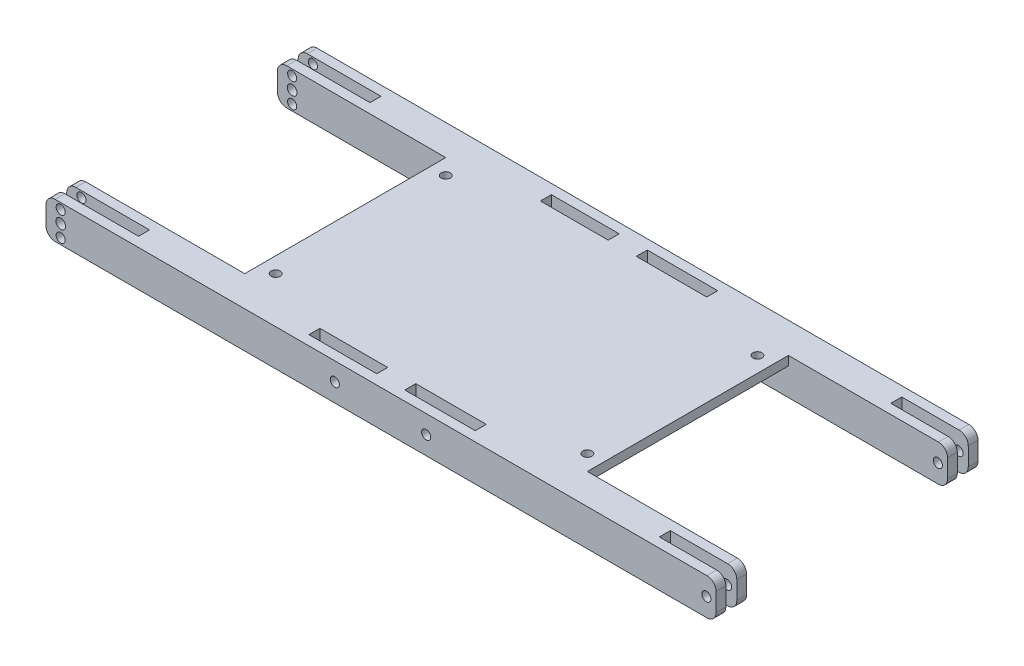
SolidWorks part; units mm, degrees
ref_plane "Front Plane" through (0, 0, 0) normal (0, 0, 1) x (1, 0, 0)
ref_plane "Top Plane" through (0, 0, 0) normal (0, 1, 0) x (1, 0, 0)
ref_plane "Right Plane" through (0, 0, 0) normal (1, 0, 0) x (0, 0, -1)
sketch "Sketch1" plane through (0, 0, 0) normal (0, 0, 1) x (1, 0, 0)
  line L0 (109.8741, 43.7425) -> (110.0523, 43.8945)
  line L1 (-103.9477, 43.8945) -> (110.0523, 43.8945)
  line L2 (-106.9477, 40.8945) -> (-106.9477, 34.8945)
  line L3 (-103.9477, 31.8945) -> (110.0523, 31.8945)
  line L4 (113.0523, 40.8945) -> (113.0523, 34.8945)
  arc A0 (-103.9477, 43.8945) -> (-106.9477, 40.8945) centre (-103.9477, 40.8945) ccw
  arc A1 (-106.9477, 34.8945) -> (-103.9477, 31.8945) centre (-103.9477, 34.8945) ccw
  arc A2 (110.0523, 31.8945) -> (113.0523, 34.8945) centre (110.0523, 34.8945) ccw
  arc A3 (110.0523, 43.8945) -> (113.0523, 40.8945) centre (110.0523, 40.8945) cw
  circle A4 centre (-102.1259, 37.8955) radius 1.6
  circle A5 centre (-102.1259, 41.8955) radius 1.5
  circle A6 centre (-102.1259, 33.8955) radius 1.5
  circle A7 centre (109.8742, 37.8918) radius 1.5
  circle A8 centre (-12.1259, 37.8955) radius 1.5
  circle A9 centre (17.8741, 37.8955) radius 1.5
  point P6 (-106.9477, 43.8955)
  point P11 (113.0523, 31.8945)
  point P14 (113.0523, 43.8945)
  dimension "D3" = 3
  dimension "D6" = 3.2
  dimension "D5" = 3
  dimension "D8" = 3
  dimension "D10" = 3
  dimension "D12" = 3
  dimension "D14" = 3
  dimension "D1" = 220
  dimension "D2" = 12
  dimension "D4" = 4
  dimension "D7" = 4
  dimension "D9" = 6
  dimension "D11" = 90
  dimension "D13" = 30
extrude "Boss-Extrude3" add sketch "Sketch1" along normal blind 3.2
pattern_linear "LPattern2" count 2 spacing 6.8 along (0, 0, 1) of bodies 103
ref_plane "Plane1" through (-103.9477, 43.8945, 3.2) normal (1, 0, 0) x (0, 0, -1)
sketch "Sketch4" plane through (0, 0, 3.2) normal (0, 0, 1) x (1, 0, 0)
  line L0 (3.0523, 31.8945) -> (3.0523, 63.7871) construction
  line L1 (-103.9477, 31.8945) -> (110.0523, 31.8945) construction
  line L2 (-103.9477, 43.8945) -> (110.0523, 43.8945) construction
  line L3 (3.0523, 43.8945) -> (7.6623, 43.8945)
  line L4 (3.0523, 43.8945) -> (-1.5577, 43.8945)
  dimension "D1" = 4.61
  dimension "D2" = 4.61
sketch "Sketch5" plane through (0, 0, 3.2) normal (0, 0, 1) x (1, 0, 0)
  line L0 (7.6623, 43.8945) -> (7.6623, 31.8945)
  line L1 (-103.9477, 31.8945) -> (110.0523, 31.8945) construction
  line L2 (-1.5577, 43.8945) -> (-1.5577, 31.8945)
  line L3 (-1.5577, 31.8945) -> (7.6623, 31.8945)
sketch "Sketch9" plane through (0, 0, 3.2) normal (0, 0, 1) x (1, 0, 0)
  line L1 (-1.5577, 43.8945) -> (7.6623, 43.8945)
  line L2 (7.6623, 43.8945) -> (7.6623, 31.8945)
  line L3 (7.6623, 31.8945) -> (-1.5577, 31.8945)
  line L4 (-1.5577, 43.8945) -> (-1.5577, 31.8945)
extrude "Boss-Extrude5" add sketch "Sketch9" along normal blind 3.7
sketch "Sketch11" plane through (0, 0, 3.2) normal (0, 0, 1) x (1, 0, 0)
  line L1 (30.7949, 43.8945) -> (91.2254, 43.8945)
  line L2 (-103.9477, 43.8945) -> (110.0523, 43.8945) construction
  line L3 (-79.6965, 43.8945) -> (-79.7588, 43.8945)
  line L4 (-79.7588, 43.8945) -> (-79.7588, 31.8945)
  line L5 (-103.9477, 31.8945) -> (110.0523, 31.8945) construction
  line L6 (-79.7588, 31.8945) -> (-23.8197, 31.8945)
  line L7 (-23.8197, 31.8945) -> (-23.8197, 43.8945)
  line L8 (-23.8197, 43.8945) -> (-79.6965, 43.8945)
  line L9 (30.7949, 43.8945) -> (30.7949, 31.8945)
  line L10 (30.7949, 31.8945) -> (91.2254, 31.8945)
  line L11 (91.2254, 43.8945) -> (91.2254, 31.8945)
extrude "Boss-Extrude6" add sketch "Sketch11" along normal blind 3.7
pattern_linear "LPattern3" count 2 spacing 76 along (0, 0, 1) of bodies 108
sketch "Sketch13" plane through (0, 43.8945, 0) normal (0, 1, 0) x (1, 0, 0)
  line L0 (-103.9477, -10) -> (110.0523, -10) construction
  line L1 (-51.7024, -10) -> (60.7994, -10)
  line L2 (-51.7024, -10) -> (-51.7024, -76)
  line L3 (-51.7024, -76) -> (60.7994, -76)
  line L4 (60.7994, -10) -> (60.7994, -76)
  line L5 (-103.9477, -76) -> (110.0523, -76) construction
extrude "Boss-Extrude8" add sketch "Sketch13" against normal blind 3 contours L2 L3 L4 L1
sketch "Sketch14" plane through (0, 43.8945, 0) normal (0, 1, 0) x (1, 0, 0)
  line L0 (-51.7024, -10) -> (-51.7024, -76) construction
  line L1 (-103.9477, -10) -> (-51.7024, -10) construction
  line L2 (-103.9477, -76) -> (-51.7024, -76) construction
  line L3 (60.7994, -10) -> (60.7994, -76) construction
  circle A0 centre (-46.6224, -15.08) radius 1.5
  circle A1 centre (55.7194, -15.08) radius 1.5
  circle A2 centre (55.7194, -70.92) radius 1.5
  circle A3 centre (-46.6224, -70.92) radius 1.5
  point P12 (-46.6224, -69.9284)
  point P15 (55.041, -70.92)
  point P18 (0, 0)
  point P19 (0, 0)
  point P20 (55.7194, -70.92)
  point P21 (55.7194, -15.08)
  dimension "D1" = 5.08
  dimension "D2" = 5.08
  dimension "D3" = 3
  dimension "D4" = 3
  dimension "D5" = 3
  dimension "D6" = 3
  dimension "D7" = 5.08
  dimension "D8" = 5.08
  dimension "D9" = 5.08
extrude "Cut-Extrude2" cut sketch "Sketch14" against normal blind 4.318 contours A1 | A2 | A0 | A3
sketch "Sketch22" plane through (0, 40.8945, 0) normal (0, -1, 0) x (1, 0, 0)
  line L0 (-51.7024, 76) -> (60.7994, 76) construction
  line L1 (-39.3253, 76) -> (-34.1504, 76)
  line L2 (-39.3253, 76) -> (-39.3253, 65.7826)
  line L3 (-39.3253, 65.7826) -> (-34.1504, 65.7826)
  line L4 (-34.1504, 76) -> (-34.1504, 65.7826)
  line L5 (-24.0853, 76) -> (-24.0853, 65.7826)
  line L6 (-24.0853, 76) -> (-18.9104, 76)
  line L7 (-18.9104, 76) -> (-18.9104, 65.7826)
  line L8 (-24.0853, 65.7826) -> (-18.9104, 65.7826)
  line L9 (-8.8453, 76) -> (-8.8453, 65.7826)
  line L10 (-8.8453, 76) -> (-3.6704, 76)
  line L11 (-3.6704, 76) -> (-3.6704, 65.7826)
  line L12 (-8.8453, 65.7826) -> (-3.6704, 65.7826)
  line L13 (6.3947, 76) -> (6.3947, 65.7826)
  line L14 (6.3947, 76) -> (11.5696, 76)
  line L15 (11.5696, 76) -> (11.5696, 65.7826)
  line L16 (6.3947, 65.7826) -> (11.5696, 65.7826)
  line L17 (21.6347, 76) -> (21.6347, 65.7826)
  line L18 (21.6347, 76) -> (26.8096, 76)
  line L19 (26.8096, 76) -> (26.8096, 65.7826)
  line L20 (21.6347, 65.7826) -> (26.8096, 65.7826)
  line L21 (36.8747, 76) -> (36.8747, 65.7826)
  line L22 (36.8747, 76) -> (42.0496, 76)
  line L23 (42.0496, 76) -> (42.0496, 65.7826)
  line L24 (36.8747, 65.7826) -> (42.0496, 65.7826)
  line L25 (-24.0853, 20.12) -> (-24.0853, 9.9026)
  line L26 (-24.0853, 20.12) -> (-18.9104, 20.12)
  line L27 (-18.9104, 20.12) -> (-18.9104, 9.9026)
  line L28 (-24.0853, 9.9026) -> (-18.9104, 9.9026)
  line L29 (-8.8453, 20.12) -> (-8.8453, 9.9026)
  line L30 (-8.8453, 20.12) -> (-3.6704, 20.12)
  line L31 (-3.6704, 20.12) -> (-3.6704, 9.9026)
  line L32 (-8.8453, 9.9026) -> (-3.6704, 9.9026)
  line L33 (6.3947, 20.12) -> (6.3947, 9.9026)
  line L34 (6.3947, 20.12) -> (11.5696, 20.12)
  line L35 (11.5696, 20.12) -> (11.5696, 9.9026)
  line L36 (6.3947, 9.9026) -> (11.5696, 9.9026)
  line L37 (21.6347, 20.12) -> (21.6347, 9.9026)
  line L38 (21.6347, 20.12) -> (26.8096, 20.12)
  line L39 (26.8096, 20.12) -> (26.8096, 9.9026)
  line L40 (21.6347, 9.9026) -> (26.8096, 9.9026)
  line L41 (36.8747, 20.12) -> (36.8747, 9.9026)
  line L42 (36.8747, 20.12) -> (42.0496, 20.12)
  line L43 (42.0496, 20.12) -> (42.0496, 9.9026)
  line L44 (36.8747, 9.9026) -> (42.0496, 9.9026)
  line L45 (-39.3253, 20.12) -> (-39.3253, 9.9026)
  line L46 (-39.3253, 20.12) -> (-34.1504, 20.12)
  line L47 (-34.1504, 20.12) -> (-34.1504, 9.9026)
  line L48 (-39.3253, 9.9026) -> (-34.1504, 9.9026)
  dimension "D1" = 6
  dimension "D2" = 2
extrude "Boss-Extrude9" add sketch "Sketch22" along normal blind 4.318
